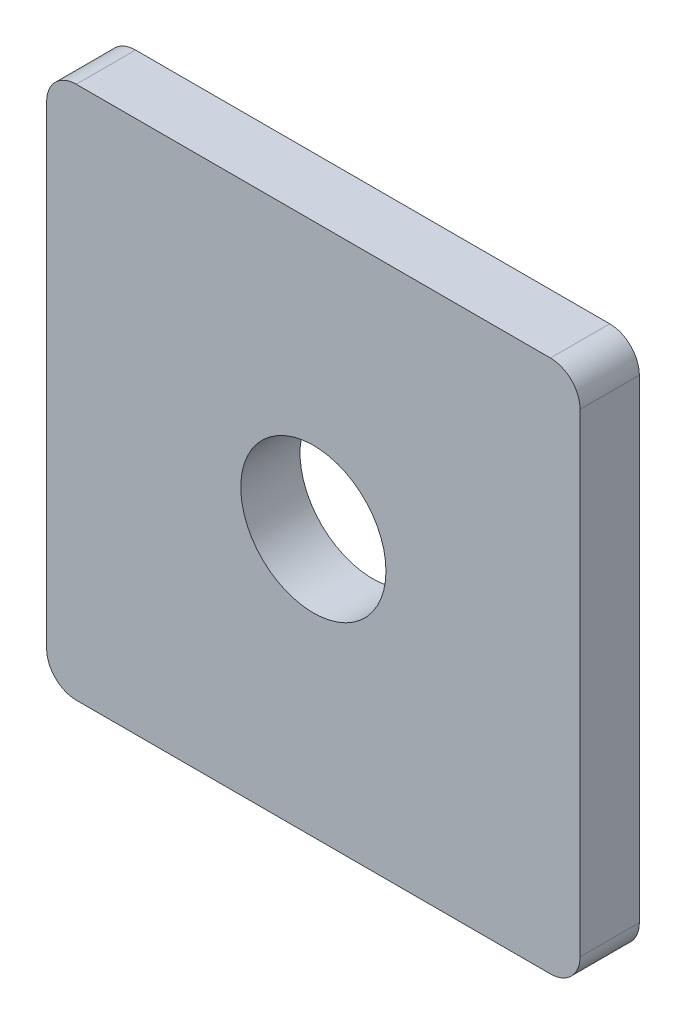
SolidWorks part; units mm, degrees
material "1060 Alloy"
ref_plane "Ebene vorne" through (0, 0, 0) normal (0, 0, 1) x (1, 0, 0)
ref_plane "Ebene oben" through (0, 0, 0) normal (0, 1, 0) x (1, 0, 0)
ref_plane "Ebene rechts" through (0, 0, 0) normal (1, 0, 0) x (0, 0, -1)
sketch "Sketch1" plane through (0, 0, 0) normal (0, 0, 1) x (1, 0, 0)
  line L1 (-9, 9) -> (9, 9)
  line L2 (-9, 9) -> (-9, -9)
  line L3 (-9, -9) -> (9, -9)
  line L4 (9, 9) -> (9, -9)
  line L5 (-9, 9) -> (9, -9) construction
  line L6 (-9, -9) -> (9, 9) construction
  circle A0 centre (0, 0) radius 2.45
  point P0 (0, 0)
  dimension "D2" = 4.9
  dimension "D1" = 18
extrude "Boss-Extrude1" add sketch "Sketch1" along normal blind 2
fillet "Fillet1" radius 1 4 edges at (-9, 9, 1) (9, -9, 1) (9, 9, 1) (-9, -9, 1)
